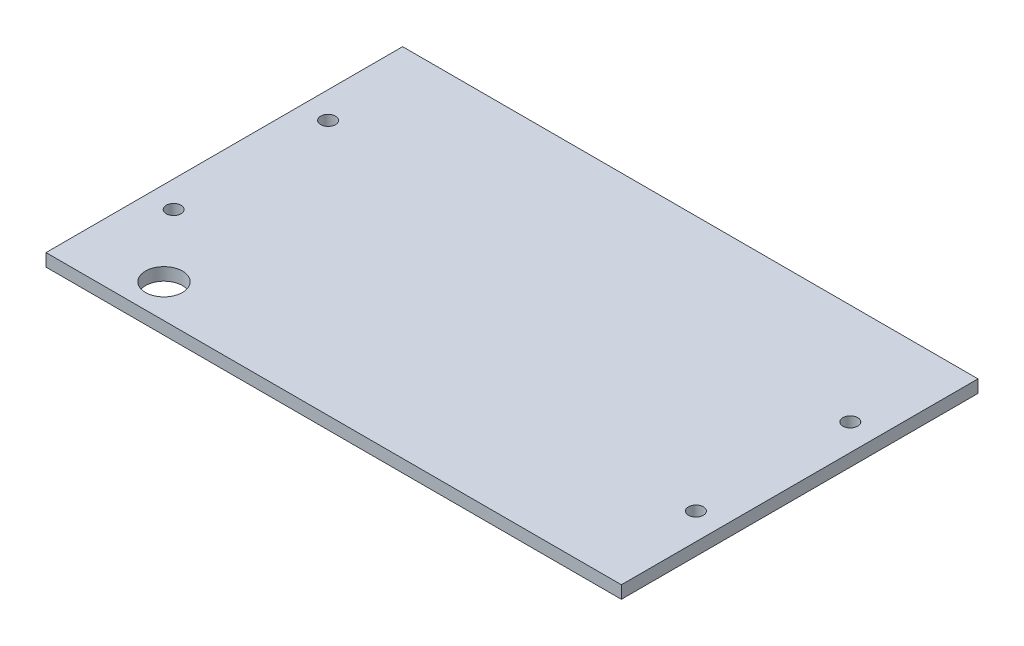
SolidWorks part; units mm, degrees
material "Acrylic (Medium-high impact)"
ref_plane "Front Plane" through (0, 0, 0) normal (0, 0, 1) x (1, 0, 0)
ref_plane "Top Plane" through (0, 0, 0) normal (0, 1, 0) x (1, 0, 0)
ref_plane "Right Plane" through (0, 0, 0) normal (1, 0, 0) x (0, 0, -1)
sketch "Sketch1" plane through (0, 0, 0) normal (0, 1, 0) x (1, 0, 0)
  line L1 (0, 0) -> (216.7839, 0)
  line L2 (0, 0) -> (0, 134.366)
  line L3 (0, 134.366) -> (216.7839, 134.366)
  line L4 (216.7839, 0) -> (216.7839, 134.366)
  circle A0 centre (31.75, 12.7) radius 6.985
  circle A1 centre (10.0076, 96.266) radius 2.794
  circle A2 centre (10.0076, 38.1) radius 2.794
  circle A3 centre (206.7763, 96.266) radius 2.794
  circle A4 centre (206.7763, 38.1) radius 2.794
  dimension "D3" = 13.97
  dimension "D6" = 5.588
  dimension "D7" = 5.588
  dimension "D8" = 5.588
  dimension "D9" = 5.588
  dimension "D1" = 216.7839
  dimension "D2" = 134.366
  dimension "D4" = 12.7
  dimension "D5" = 31.75
  dimension "D10" = 38.1
  dimension "D11" = 38.1
  dimension "D12" = 10.0076
  dimension "D13" = 10.0076
  dimension "D14" = 38.1
  dimension "D15" = 38.1
  dimension "D16" = 10.0076
  dimension "D17" = 10.0076
extrude "Boss-Extrude1" add sketch "Sketch1" along normal blind 4.7625
